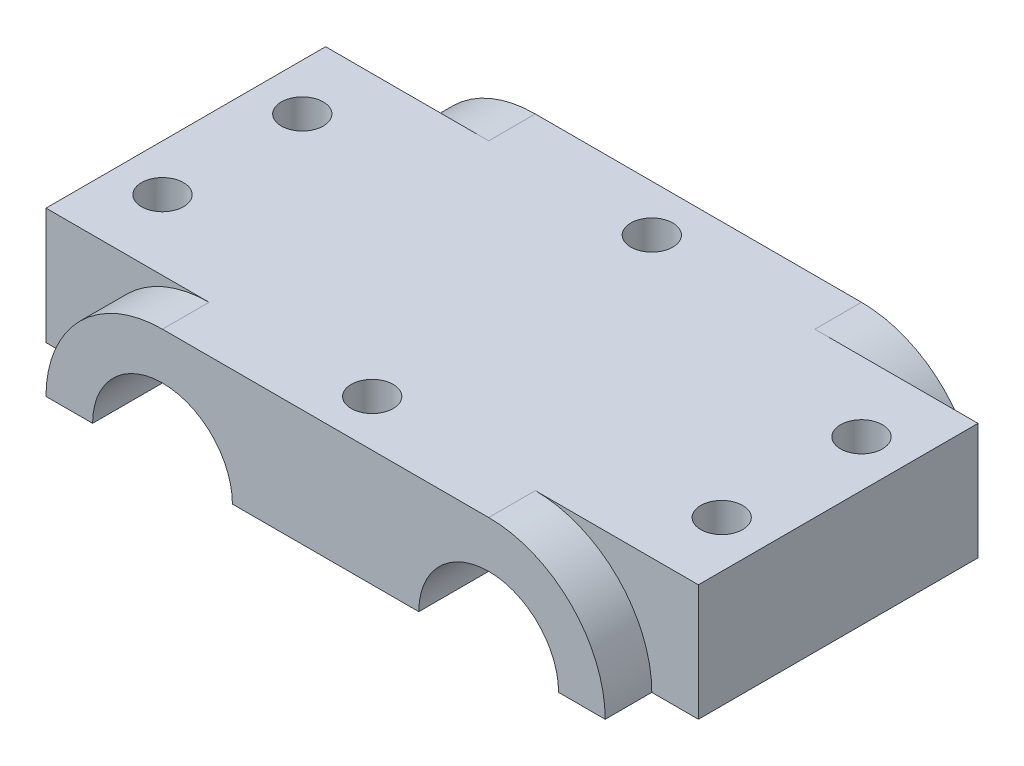
SolidWorks part; units mm, degrees
ref_plane "Front Plane" through (0, 0, 0) normal (0, 0, 1) x (1, 0, 0)
ref_plane "Top Plane" through (0, 0, 0) normal (0, 1, 0) x (1, 0, 0)
ref_plane "Right Plane" through (0, 0, 0) normal (1, 0, 0) x (0, 0, -1)
sketch "Sketch1" plane through (0, 0, 0) normal (0, 0, 1) x (1, 0, 0)
  line L0 (0, 0) -> (0, 12.5)
  line L1 (0, 12.5) -> (70, 12.5)
  line L2 (70, 12.5) -> (70, 0)
  line L3 (70, 0) -> (0, 0)
  dimension "D1" = 12.5
  dimension "D2" = 70
extrude "Boss-Extrude1" add sketch "Sketch1" along normal blind 30
ref_plane "Plane1" through (0, 0, -5) normal (0, 0, 1) x (1, 0, 0)
sketch "Sketch2" plane through (0, 0, -5) normal (0, 0, 1) x (1, 0, 0)
  line L0 (35, 0) -> (25, 0)
  line L1 (0, 0) -> (70, 0) construction
  line L2 (70, 12.5) -> (0, 12.5) construction
  line L3 (17.5, 12.5) -> (52.5, 12.5)
  line L4 (65, 0) -> (60, 0)
  line L5 (10, 0) -> (5, 0)
  line L6 (45, 0) -> (35, 0)
  arc A0 (5, 0) -> (17.5, 12.5) centre (17.5, 0) cw
  arc A1 (52.5, 12.5) -> (65, 0) centre (52.5, 0) cw
  arc A2 (25, 0) -> (10, 0) centre (17.5, 0) ccw
  arc A3 (60, 0) -> (45, 0) centre (52.5, 0) ccw
  dimension "D1" = 12.5
  dimension "D2" = 12.5
  dimension "D5" = 15
  dimension "D6" = 15
  dimension "D3" = 35
  dimension "D4" = 17.5
extrude "Boss-Extrude2" add sketch "Sketch2" along normal blind 40
sketch "Sketch5" plane through (0, 0, 0) normal (0, 0, -1) x (-1, 0, 0)
  line L0 (-25, 0) -> (-10, 0) construction
  line L1 (-60, 0) -> (-45, 0) construction
  line L2 (-25, 0) -> (-10, 0)
  line L3 (-60, 0) -> (-45, 0)
  arc A0 (-10, 0) -> (-25, 0) centre (-17.5, 0) ccw construction
  arc A1 (-45, 0) -> (-60, 0) centre (-52.5, 0) ccw construction
  arc A2 (-10, 0) -> (-25, 0) centre (-17.5, 0) ccw
  arc A3 (-45, 0) -> (-60, 0) centre (-52.5, 0) ccw
extrude "Cut-Extrude1" cut sketch "Sketch5" against normal blind 40
ref_plane "Plane2" through (0, 12.5, 0) normal (0, 1, 0) x (1, 0, 0)
sketch "Sketch6" plane through (0, 12.5, 0) normal (0, 1, 0) x (1, 0, 0)
  line L0 (17.5, 0) -> (5, 0) construction
  line L1 (0, -30) -> (0, 0) construction
  line L2 (70, 0) -> (52.5, 0) construction
  line L3 (70, -30) -> (70, 0) construction
  line L4 (5, 0) -> (5, 5) construction
  line L5 (52.5, -35) -> (17.5, -35) construction
  circle A0 centre (5, -7.5) radius 2.25
  circle A1 centre (5, -22.5) radius 2.25
  circle A2 centre (35, 0) radius 2.25
  circle A3 centre (35, -30) radius 2.25
  circle A4 centre (65, -7.5) radius 2.25
  circle A5 centre (65, -22.5) radius 2.25
  dimension "D1" = 4.5
  dimension "D6" = 4.5
  dimension "D2" = 15
  dimension "D3" = 7.5
  dimension "D4" = 5
  dimension "D5" = 5
  dimension "D7" = 15
  dimension "D8" = 7.5
  dimension "D9" = 5
  dimension "D10" = 5
  dimension "D11" = 30
  dimension "D12" = 30
  dimension "D13" = 5
extrude "Cut-Extrude2" cut sketch "Sketch6" against normal blind 40
